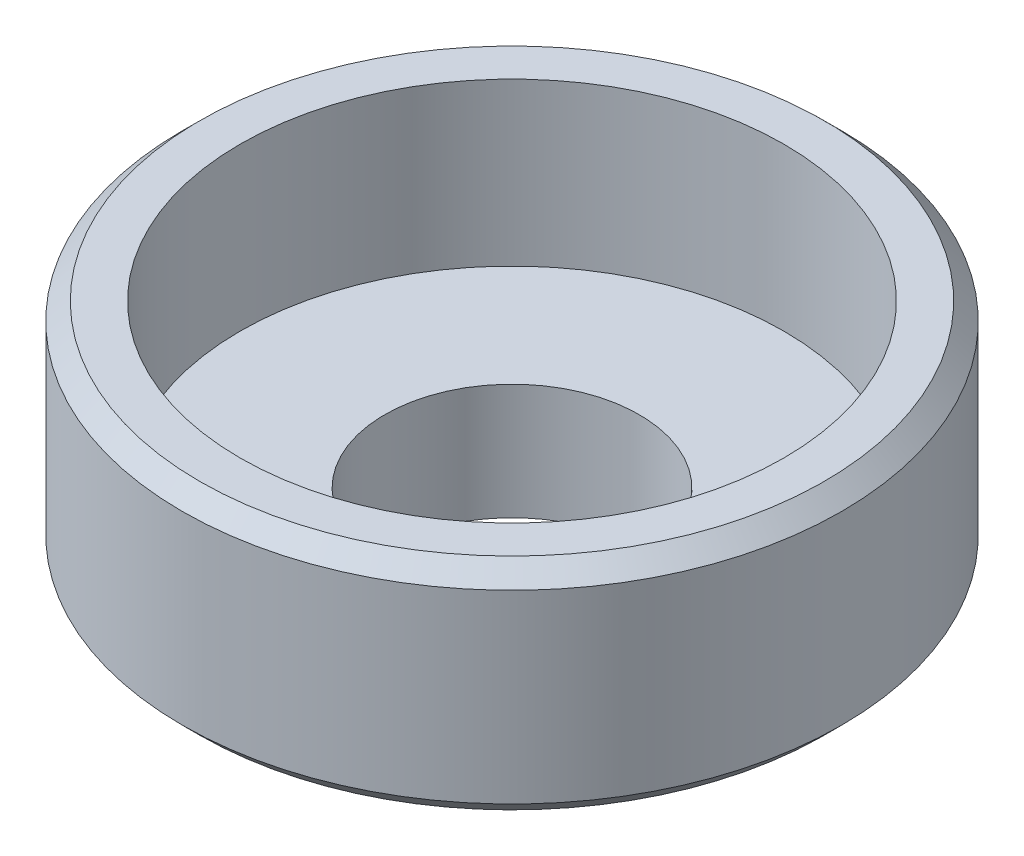
SolidWorks part; units mm, degrees
material "Сталь 3 ГОСТ 535-88"
ref_plane "Спереди" through (0, 0, 0) normal (0, 0, 1) x (1, 0, 0)
ref_plane "Сверху" through (0, 0, 0) normal (0, 1, 0) x (1, 0, 0)
ref_plane "Справа" through (0, 0, 0) normal (1, 0, 0) x (0, 0, -1)
sketch "Эскиз1" plane through (0, 0, 0) normal (1, 0, 0) x (0, 0, -1)
  line L0 (0, 19.7712) -> (0, -17.6113) construction
  line L2 (-15, 0) -> (-28.5, 0)
  line L3 (-28.5, 0) -> (-28.5, 19)
  line L4 (-28.5, 19) -> (-23.5, 19)
  line L5 (-23.5, 19) -> (-23.5, 5)
  line L6 (-23.5, 5) -> (-11, 5)
  line L7 (-15, 0) -> (-15, -5)
  line L8 (-15, -5) -> (-11, -5)
  line L9 (-11, -5) -> (-11, 5)
  dimension "D1" = 57
  dimension "D2" = 47
  dimension "D3" = 22
  dimension "D4" = 19
  dimension "D5" = 14
  dimension "D6" = 30
  dimension "D7" = 5
revolve "Повернуть1" add sketch "Эскиз1" angle 360 about L0
chamfer "Фаска1" distance 1.5 angle 45 3 edges at (0, 19, 28.5) (0, 0, 28.5) (0, -5, 15)
